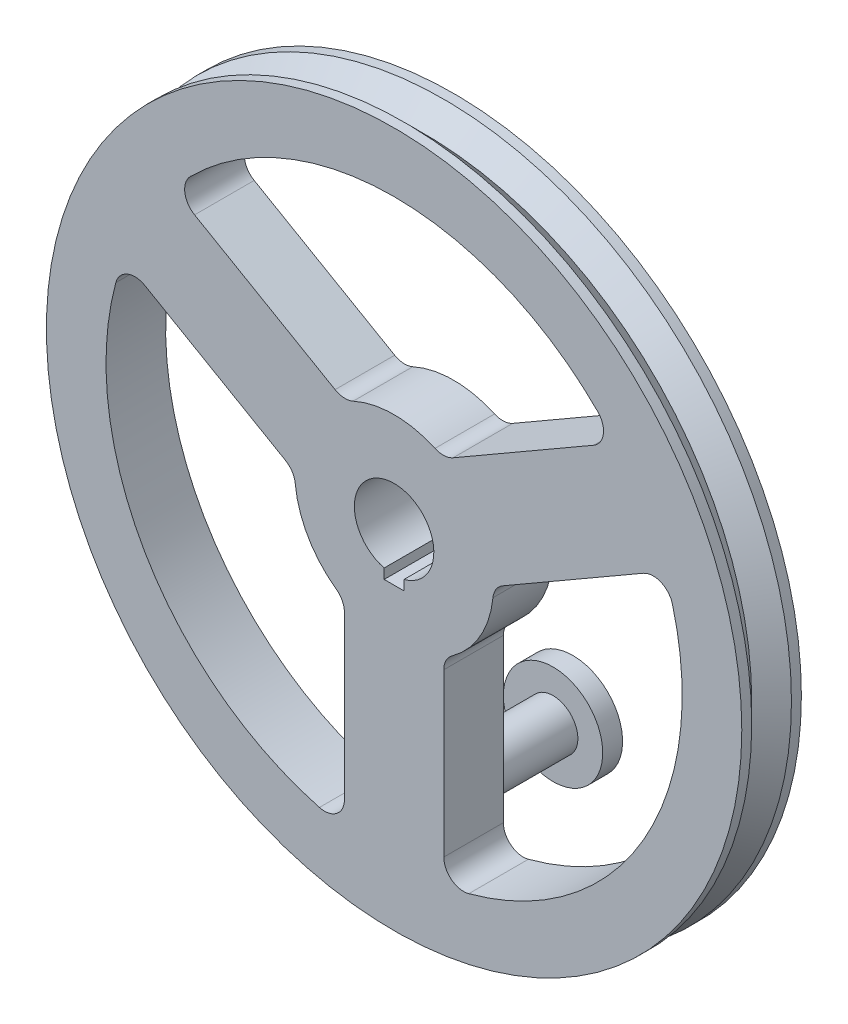
SolidWorks part; units mm, degrees
ref_plane "Front Plane" through (0, 0, 0) normal (0, 0, 1) x (1, 0, 0)
ref_plane "Top Plane" through (0, 0, 0) normal (0, 1, 0) x (1, 0, 0)
ref_plane "Right Plane" through (0, 0, 0) normal (1, 0, 0) x (0, 0, -1)
sketch "Sketch1" plane through (0, 0, 0) normal (0, 0, 1) x (1, 0, 0)
  line L0 (-285.8807, 0) -> (264.6211, 0) construction
  line L1 (0, 262.4377) -> (0, -290.1131) construction
  line L6 (25, -48.734) -> (25, -130.384)
  line L7 (54.7049, 2.7164) -> (125.4159, 43.5414)
  line L8 (-25, -48.734) -> (-25, -130.384)
  line L9 (-54.7049, 2.7164) -> (-125.4159, 43.5414)
  line L10 (-29.7049, 46.0176) -> (-100.4159, 86.8427)
  line L11 (29.7049, 46.0176) -> (100.4159, 86.8427)
  line L12 (-5, -19.3649) -> (-5, -24.3649)
  line L13 (5, -19.3649) -> (5, -24.3649)
  line L14 (-5, -24.3649) -> (5, -24.3649)
  circle A0 centre (0, 0) radius 175
  arc A1 (37.5926, -140.0421) -> (140.0763, 37.4649) centre (0, 0) ccw
  arc A2 (29.1667, -40.6116) -> (49.754, -4.9533) centre (0, 0) ccw
  arc A3 (5, -19.3649) -> (-5, -19.3649) centre (0, 0) ccw
  arc A6 (25, -130.384) -> (37.5926, -140.0421) centre (35, -130.384) ccw
  arc A7 (-140.0763, 37.4649) -> (-37.5926, -140.0421) centre (0, 0) ccw
  arc A8 (125.4159, 43.5414) -> (140.0763, 37.4649) centre (130.4159, 34.8811) cw
  arc A9 (25, -48.734) -> (29.1667, -40.6116) centre (35, -48.734) cw
  arc A10 (54.7049, 2.7164) -> (49.754, -4.9533) centre (59.7049, -5.9439) ccw
  arc A11 (-25, -130.384) -> (-37.5926, -140.0421) centre (-35, -130.384) cw
  arc A12 (-49.754, -4.9533) -> (-29.1667, -40.6116) centre (0, 0) ccw
  arc A13 (-125.4159, 43.5414) -> (-140.0763, 37.4649) centre (-130.4159, 34.8811) ccw
  arc A14 (-54.7049, 2.7164) -> (-49.754, -4.9533) centre (-59.7049, -5.9439) cw
  arc A15 (-25, -48.734) -> (-29.1667, -40.6116) centre (-35, -48.734) ccw
  arc A16 (102.4837, 102.5772) -> (-102.4837, 102.5772) centre (0, 0) ccw
  arc A17 (-100.4159, 86.8427) -> (-102.4837, 102.5772) centre (-95.4159, 95.5029) cw
  arc A18 (20.5874, 45.5649) -> (-20.5874, 45.5649) centre (0, 0) ccw
  arc A19 (100.4159, 86.8427) -> (102.4837, 102.5772) centre (95.4159, 95.5029) ccw
  arc A20 (29.7049, 46.0176) -> (20.5874, 45.5649) centre (24.7049, 54.6779) cw
  arc A21 (-29.7049, 46.0176) -> (-20.5874, 45.5649) centre (-24.7049, 54.6779) ccw
  point P20 (-25, -142.8286)
  point P23 (25, -142.8286)
  point P29 (25, -43.3013)
  point P32 (50, 0)
  point P53 (0, 0)
  dimension "D1" = 350
  dimension "D2" = 145
  dimension "D3" = 50
  dimension "D4" = 40
  dimension "D6" = 25
  dimension "D9" = 10
  dimension "D10" = 145
  dimension "D11" = 10
  dimension "D12" = 10
  dimension "D5" = 120
  dimension "D14" = 10
  dimension "D15" = 5
  dimension "D13" = 3
extrude "Boss-Extrude4" add sketch "Sketch1" along normal mid plane 30
sketch "Sketch2" plane through (0, 0, -15) normal (0, 0, -1) x (-1, 0, 0)
  circle A0 centre (0, -125) radius 12.5
  dimension "D1" = 25
  dimension "D2" = 125
extrude "Boss-Extrude5" add sketch "Sketch2" along normal blind 50
sketch "Sketch3" plane through (0, 0, -65) normal (0, 0, -1) x (-1, 0, 0)
  circle A0 centre (0, -125) radius 25
  dimension "D1" = 50
extrude "Boss-Extrude6" add sketch "Sketch3" along normal blind 10
sketch "Sketch4" plane through (0, 0, 0) normal (0, 1, 0) x (1, 0, 0)
  line L0 (-175, -15) -> (175, -15) construction
  line L1 (-175, 15) -> (-175, -15) construction
  line L2 (-175, -10) -> (-165, 0)
  line L3 (-165, 0) -> (-175, 10)
  line L5 (175, 15) -> (-175, 15) construction
  line L7 (0, -35.7092) -> (0, 47.9516) construction
  line L8 (-175, 10) -> (-175, -10)
  dimension "D1" = 5
  dimension "D2" = 5
  dimension "D3" = 10
  dimension "D4" = 15
revolve "Cut-Revolve1" cut sketch "Sketch4" angle 360 about L7
